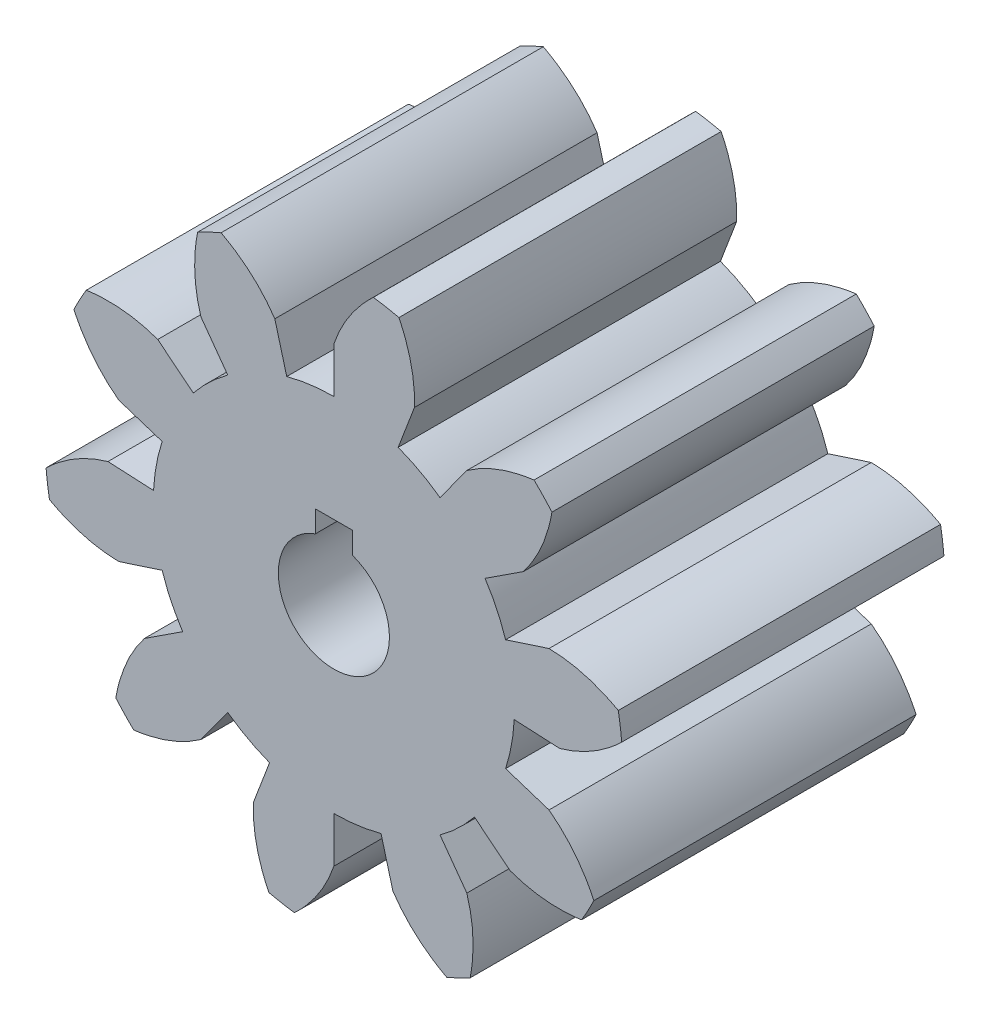
SolidWorks part; units mm, degrees
ref_plane "Front Plane" through (0, 0, 0) normal (0, 0, 1) x (1, 0, 0)
ref_plane "Top Plane" through (0, 0, 0) normal (0, 1, 0) x (1, 0, 0)
ref_plane "Right Plane" through (0, 0, 0) normal (1, 0, 0) x (0, 0, -1)
sketch "Sketch1" plane through (0, 0, 0) normal (0, 0, 1) x (1, 0, 0)
  line L0 (0, 30.535) -> (19.2447, 23.7072) construction
  line L1 (19.2447, 23.7072) -> (29.8828, 6.2771) construction
  line L2 (29.8828, 6.2771) -> (27.157, -13.9601) construction
  line L3 (27.157, -13.9601) -> (12.2861, -27.9542) construction
  line L4 (19.2447, 23.7072) -> (3.3907, 36.5768) construction
  line L5 (29.8828, 6.2771) -> (21.4873, 46.2449) construction
  line L6 (27.157, -13.9601) -> (55.1641, 40.5228) construction
  line L7 (12.2861, -27.9542) -> (87.0626, 4.9108) construction
  line L8 (0.7914, 32.4904) -> (10.8326, 30.6416) construction
  line L9 (5.812, 31.566) -> (0, 0) construction
  line L10 (0, 30.535) -> (0, 0)
  line L11 (0, 0) -> (10.8756, 28.5326)
  circle A0 centre (0, 0) radius 39
  circle A1 centre (0, 0) radius 32.5 construction
  circle A2 centre (0, 0) radius 30.535 construction
  circle A3 centre (0, 0) radius 24.375
  spline S0 degree 3 poles (0, 30.535) (3.0693, 39.5236) (39.5395, 59.0602) (77.9422, 29.6488) (87.0626, 4.9108) knots 0 0 0 0 0.25084 1 1 1 1
  spline S1 degree 3 poles (10.8756, 28.5326) (11.209, 38.0249) (-15.9111, 69.2699) (-62.2709, 55.4651) (-79.6041, 35.5977) knots 0 0 0 0 0.25084 1 1 1 1
  dimension "D1" = 78
  dimension "D2" = 65
  dimension "D3" = 61.07
  dimension "D4" = 48.75
  dimension "D5" = 20.42
  dimension "D6" = 20.42
  dimension "D7" = 40.84
  dimension "D8" = 61.26
  dimension "D9" = 81.68
  dimension "D10" = 10.21
extrude "Boss-Extrude1" add sketch "Sketch1" along normal blind 43.5 contours L10 A3 L11 | L11 A3 L10 | L11 S1 A0 S0 L10 A3
pattern_circular "CirPattern1" count 10 over 360 of "Boss-Extrude1"
sketch "Sketch2" plane through (0, 0, 43.5) normal (0, 0, 1) x (1, 0, 0)
  circle A0 centre (0, 0) radius 7.5
  dimension "D1" = 15
extrude "Cut-Extrude1" cut sketch "Sketch2" against normal through all
sketch "Sketch3" plane through (0, 0, 43.5) normal (0, 0, 1) x (1, 0, 0)
  line L0 (0, 7.5) -> (0, 0) construction
  line L6 (-2.5, 10) -> (2.5, 10)
  line L7 (-2.5, 10) -> (-2.5, 5)
  line L8 (-2.5, 5) -> (2.5, 5)
  line L9 (2.5, 10) -> (2.5, 5)
  line L10 (-2.5, 10) -> (2.5, 5) construction
  line L11 (-2.5, 5) -> (2.5, 10) construction
  circle A0 centre (0, 0) radius 7.5 construction
  point P0 (0, 7.5)
  dimension "D1" = 5
  dimension "D2" = 5
extrude "Cut-Extrude2" cut sketch "Sketch3" against normal through all
